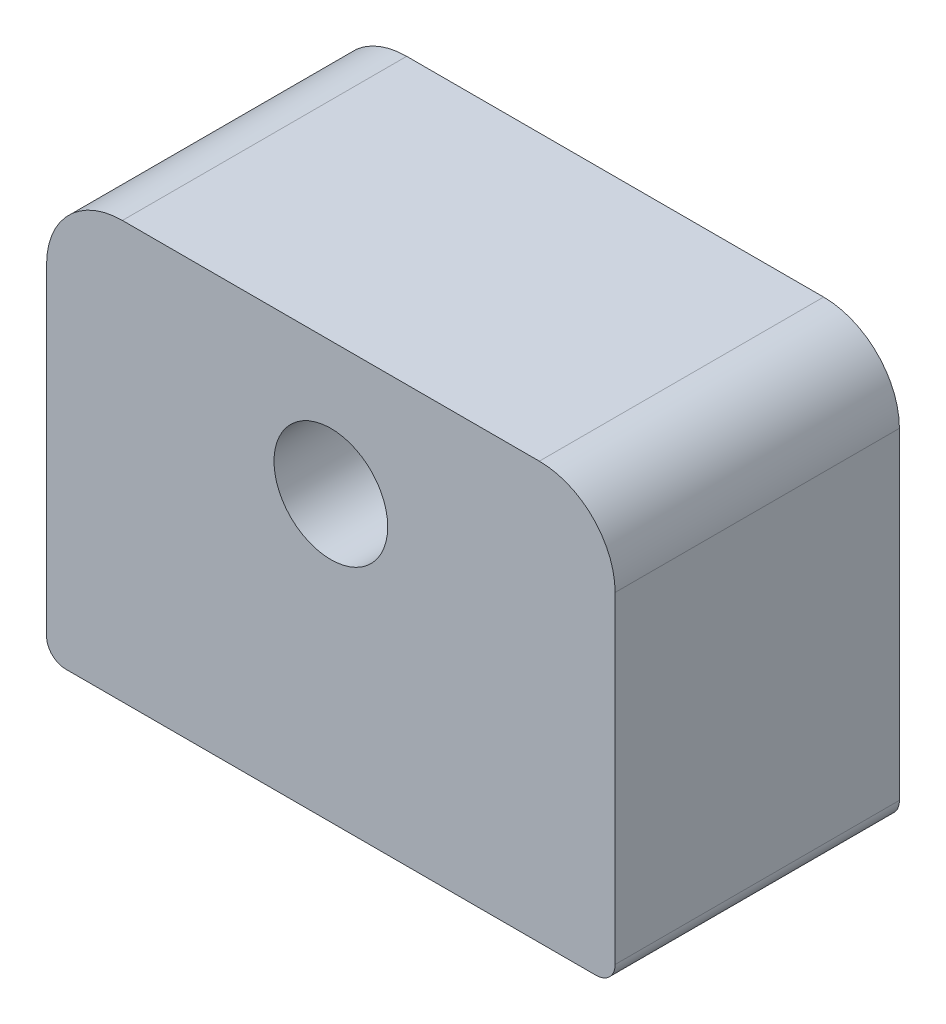
SolidWorks part; units mm, degrees
ref_plane "Plan de face" through (0, 0, 0) normal (0, 0, 1) x (1, 0, 0)
ref_plane "Plan de dessus" through (0, 0, 0) normal (0, 1, 0) x (1, 0, 0)
ref_plane "Plan de droite" through (0, 0, 0) normal (1, 0, 0) x (0, 0, -1)
sketch "Esquisse1" plane through (0, 0, 0) normal (0, 0, 1) x (1, 0, 0)
  line L0 (7.5, 0) -> (-7.5, 0) construction
  line L1 (-7.5, 5.5) -> (7.5, 5.5)
  line L2 (-7.5, 5.5) -> (-7.5, -5.5)
  line L3 (-7.5, -5.5) -> (7.5, -5.5)
  line L4 (7.5, 5.5) -> (7.5, -5.5)
  dimension "D1" = 15
  dimension "D2" = 11
extrude "Boss.-Extru.1" add sketch "Esquisse1" along normal blind 7.5
sketch "Esquisse2" plane through (0, 0, 7.5) normal (0, 0, 1) x (1, 0, 0)
  line L0 (0, 0) -> (0, 2) construction
  line L1 (7.5, 5.5) -> (-7.5, 5.5) construction
  circle A0 centre (0, 2) radius 1.5
  dimension "D2" = 3
  dimension "D1" = 3.5
extrude "Enlèv. mat.-Extru.1" cut sketch "Esquisse2" against normal through all
fillet "Congé1" radius 2 2 edges at (7.5, 5.5, 3.75) (-7.5, 5.5, 3.75)
fillet "Congé2" radius 0.5 2 edges at (7.5, -5.5, 3.75) (-7.5, -5.5, 3.75)
